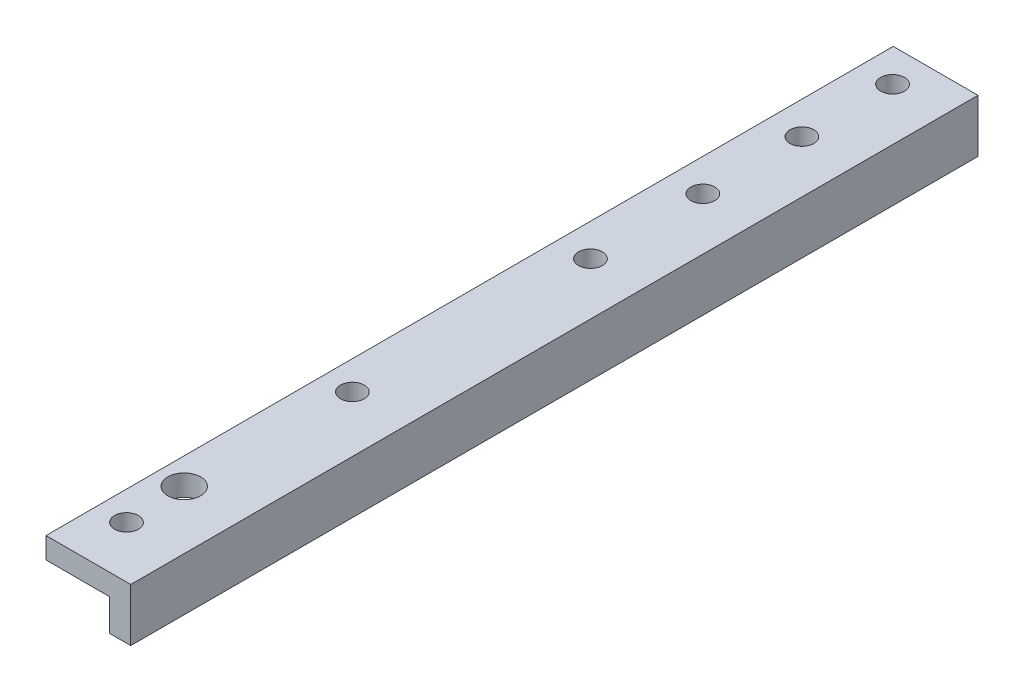
SolidWorks part; units mm, degrees
material "Plain Carbon Steel"
ref_plane "Front Plane" through (0, 0, 0) normal (0, 0, 1) x (1, 0, 0)
ref_plane "Top Plane" through (0, 0, 0) normal (0, 1, 0) x (1, 0, 0)
ref_plane "Right Plane" through (0, 0, 0) normal (1, 0, 0) x (0, 0, -1)
sketch "Sketch1" plane through (0, 0, 0) normal (0, 0, 1) x (1, 0, 0)
  line L11 (4, -4) -> (16, -4)
  line L13 (16, 0) -> (4, 0)
  line L18 (16, 0) -> (20, 0)
  line L19 (20, 0) -> (20, -10)
  line L20 (4, 0) -> (4, -4)
  line L21 (16, -4) -> (16, -10)
  line L22 (16, -10) -> (20, -10)
  point P0 (0, 0)
  dimension "D1" = 4
  dimension "D2" = 4
  dimension "D3" = 10
extrude "Boss-Extrude1" add sketch "Sketch1" along normal blind 160
sketch "Sketch2" plane through (20, 0, 0) normal (1, 0, 0) x (0, 0, -1)
  line L1 (-120, -8) -> (-160, -8)
  line L3 (-120, -10) -> (-160, -10)
  line L5 (-160, -10) -> (-160, -8)
  line L7 (-120, -10) -> (-120, -8)
  line L8 (-160, -10) -> (0, -10) construction
  line L9 (-160, -10) -> (-160, 0) construction
  point P2 (-140, -8)
  point P3 (-140.2245, -8)
  dimension "D1" = 2
  dimension "D2" = 2
  dimension "D3" = 40
extrude "Cut-Extrude1" [suppressed] cut sketch "Sketch2" against normal up to surface (4 mm away)
hole_wizard "M4 Clearance Hole1" positions "Sketch3" profile "Sketch4" hole size "M4" standard "ISO" end condition through all
sketch "Sketch3" plane through (0, -4, 0) normal (0, -1, 0) x (-1, 0, 0)
  point P0 (-10.1289, -6.2673)
  point P2 (-10.1289, -23.3816)
  point P4 (-10.1289, -42.0932)
  point P6 (-10.1289, -63.3149)
  point P8 (-9.4443, -107.5838)
  point P10 (-9.4443, -150.2448)
sketch "Sketch4" plane through (10.1289, -4, 6.2673) normal (1, 0, 0) x (0, 0, -1)
  line L0 (0, 0) -> (0, 4)
  line L1 (0, 4) -> (2.25, 4)
  line L2 (2.25, 4) -> (2.25, 0)
  line L5 (2.25, 0) -> (0, 0)
  line L11 (0, -6.35) -> (0, 107.95) construction
  dimension "Thru Hole Dia." = 4.5
  dimension "Thru Hole Depth" = 4
sketch "Sketch5" plane through (0, -4, 0) normal (0, -1, 0) x (1, 0, 0)
  circle A0 centre (9, 138.8979) radius 3.1
extrude "Cut-Extrude2" cut sketch "Sketch5" against normal up to surface (7 mm away)
